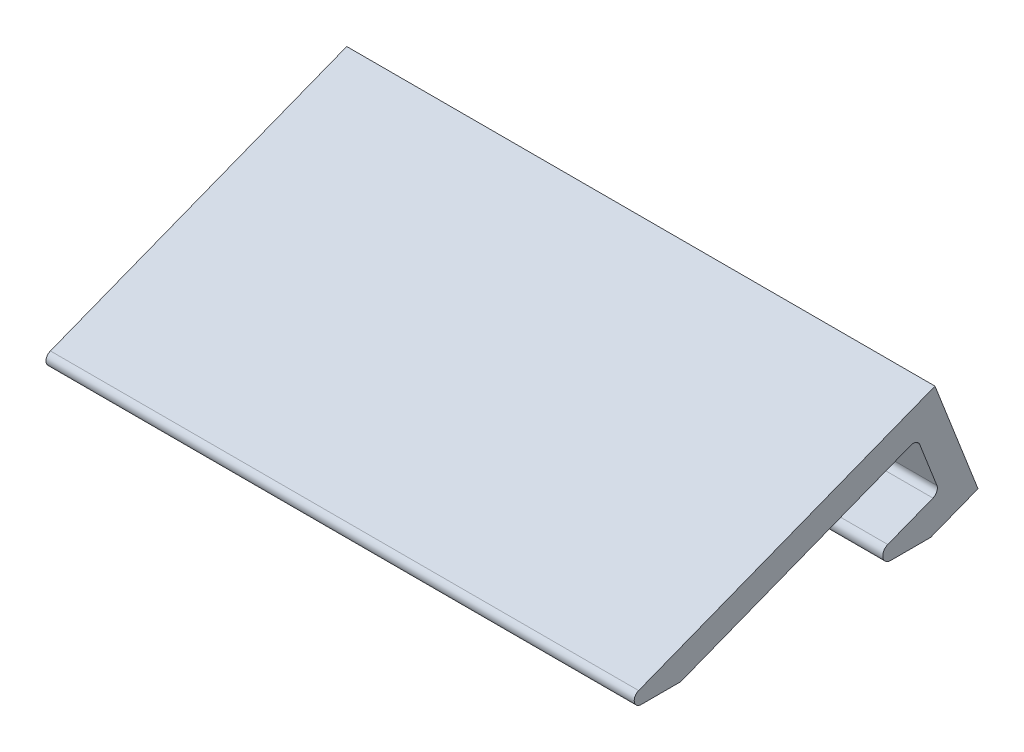
SolidWorks part; units mm, degrees
ref_plane "Ebene vorne" through (0, 0, 0) normal (0, 0, 1) x (1, 0, 0)
ref_plane "Ebene oben" through (0, 0, 0) normal (0, 1, 0) x (1, 0, 0)
ref_plane "Ebene rechts" through (0, 0, 0) normal (1, 0, 0) x (0, 0, -1)
sketch "Skizze1" plane through (0, 0, 0) normal (1, 0, 0) x (0, 0, -1)
  line L0 (49.5691, 19.3175) -> (477.2807, 186)
  line L1 (477.2807, 186) -> (539.3723, 26.6713)
  line L2 (539.3723, 26.6713) -> (470.933, 0)
  line L3 (470.933, 0) -> (413.328, 0)
  line L4 (409.1771, 22.0831) -> (474.3761, 47.4916)
  line L5 (480.0624, 60.4402) -> (455.371, 123.799)
  line L6 (442.4225, 129.4854) -> (110.1598, 0)
  line L7 (110.1598, 0) -> (53.2002, 0)
  arc A0 (413.328, 0) -> (409.1771, 22.0831) centre (413.328, 11.4317) cw
  arc A1 (49.5691, 19.3175) -> (53.2002, 0) centre (53.2002, 10) ccw
  arc A2 (455.371, 123.799) -> (442.4225, 129.4854) centre (446.0536, 120.1679) ccw
  arc A3 (474.3761, 47.4916) -> (480.0624, 60.4402) centre (470.745, 56.8091) ccw
  point P21 (0, 0)
  point P22 (43.3723, 8.1527)
  dimension "D7" = 10
  dimension "D8" = 10
  dimension "D9" = 10
  dimension "D1" = 171
  dimension "D2" = 186
  dimension "D3" = 43
  dimension "D4" = 496
  dimension "D5" = 43
  dimension "D6" = 40
extrude "Aufsatz-Linear austragen1" add sketch "Skizze1" along normal blind 849
sketch "Skizze2" plane through (0, 0, 0) normal (0, 0.9317, 0.3631) x (1, 0, 0)
  line L0 (22.1479, 20.0986) -> (1888.8146, 20.0986) construction
  line L1 (19.7657, 336.6032) -> (588.7092, 336.6032) construction
sketch "Skizze3" plane through (0, 186, -477.2807) normal (0, 0.3631, -0.9317) x (-1, 0, 0)
  line L0 (-668.9961, -55.7504) -> (-75.2771, -55.7504) construction
